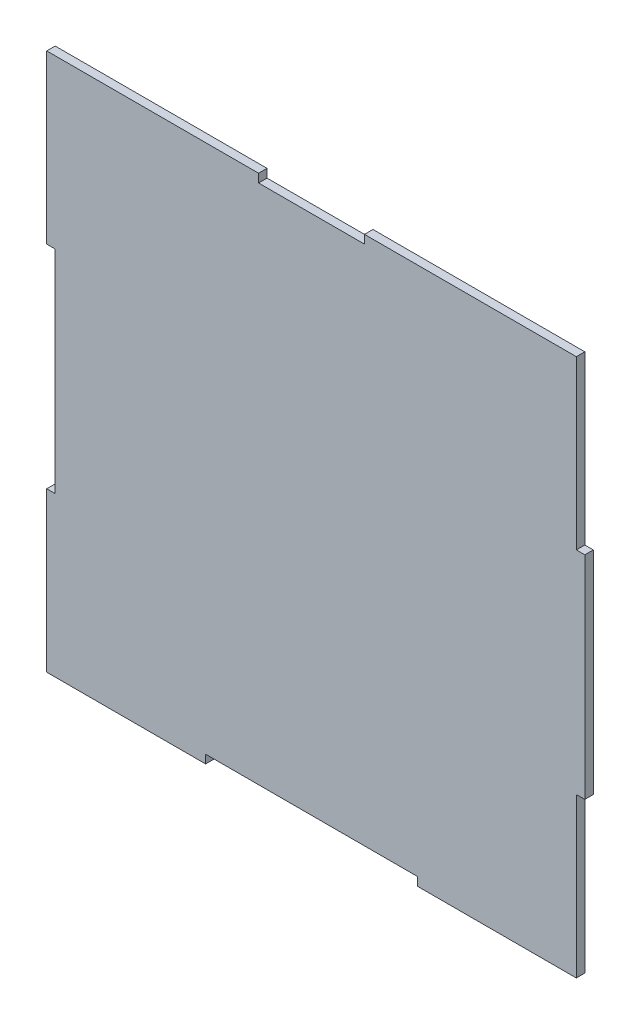
SolidWorks part; units mm, degrees
ref_plane "Front Plane" through (0, 0, 0) normal (0, 0, 1) x (1, 0, 0)
ref_plane "Top Plane" through (0, 0, 0) normal (0, 1, 0) x (1, 0, 0)
ref_plane "Right Plane" through (0, 0, 0) normal (1, 0, 0) x (0, 0, -1)
sketch "Sketch1" plane through (0, 0, 0) normal (0, 0, 1) x (1, 0, 0)
  line L0 (-2.1815, -124.7277) -> (-2.1815, -49.7277)
  line L1 (-2.1815, -49.7277) -> (1.8185, -49.7277)
  line L2 (1.8185, -49.7277) -> (1.8185, 50.2723)
  line L3 (1.8185, 50.2723) -> (-2.1815, 50.2723)
  line L4 (-2.1815, 50.2723) -> (-2.1815, 125.2723)
  line L10 (-252.1815, 125.2723) -> (-252.1815, 50.2723)
  line L11 (-252.1815, 50.2723) -> (-248.1815, 50.2723)
  line L12 (-248.1815, 50.2723) -> (-248.1815, -49.7277)
  line L13 (-248.1815, -49.7277) -> (-252.1815, -49.7277)
  line L14 (-252.1815, -49.7277) -> (-252.1815, -124.7277)
  line L15 (-252.1815, -124.7277) -> (-177.1815, -124.7277)
  line L16 (-177.1815, -124.7277) -> (-177.1815, -120.7277)
  line L17 (-177.1815, -120.7277) -> (-77.1815, -120.7277)
  line L18 (-77.1815, -120.7277) -> (-77.1815, -124.7277)
  line L19 (-77.1815, -124.7277) -> (-2.1815, -124.7277)
  line L20 (-252.1815, 125.2723) -> (-252.1815, 129.2723)
  line L21 (-252.1815, 129.2723) -> (-152.1815, 129.2723)
  line L22 (-152.1815, 129.2723) -> (-152.1815, 125.2723)
  line L23 (-323.1815, 125.2723) -> (-123.1815, 125.2723) construction
  line L24 (-152.1815, 125.2723) -> (-102.1815, 125.2723)
  line L25 (-102.1815, 125.2723) -> (-102.1815, 129.2723)
  line L26 (-102.1815, 129.2723) -> (-2.1815, 129.2723)
  line L27 (-2.1815, 129.2723) -> (-2.1815, 125.2723)
  dimension "D2" = 250
extrude "Boss-Extrude1" add sketch "Sketch1" along normal blind 4
